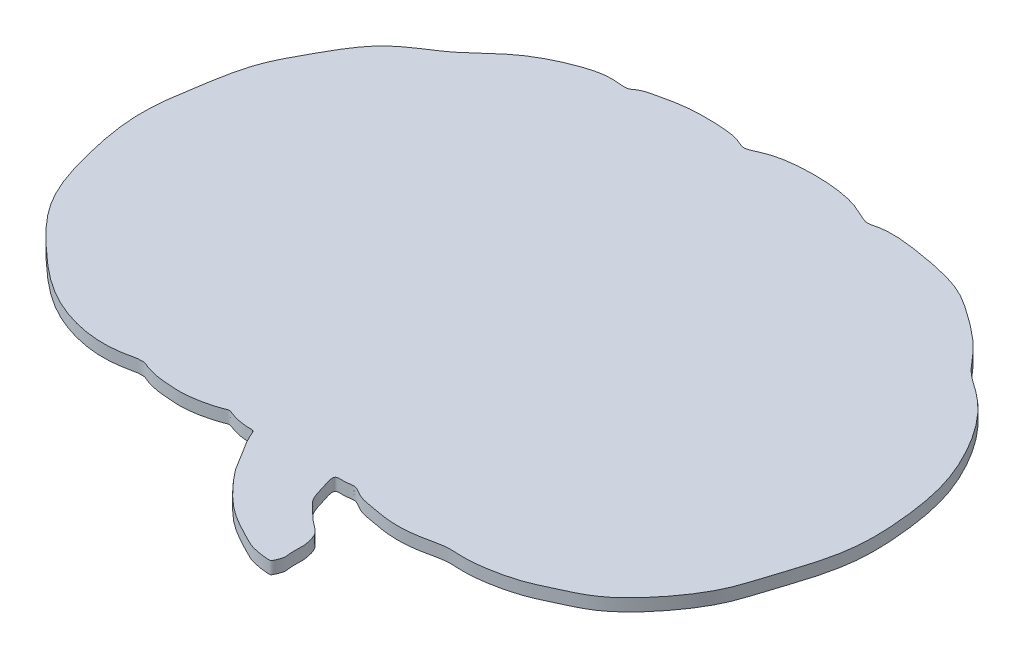
SolidWorks part; units mm, degrees
ref_plane "Front Plane" through (0, 0, 0) normal (0, 0, 1) x (1, 0, 0)
ref_plane "Top Plane" through (0, 0, 0) normal (0, 1, 0) x (1, 0, 0)
ref_plane "Right Plane" through (0, 0, 0) normal (1, 0, 0) x (0, 0, -1)
sketch "Sketch2" plane through (0, 0, 0) normal (0, 1, 0) x (1, 0, 0)
  line L1 (49.7423, 68.9433) -> (-50.2577, 68.9433)
  line L2 (49.7423, 68.9433) -> (49.7423, -31.0567)
  line L3 (49.7423, -31.0567) -> (-50.2577, -31.0567)
  line L4 (-50.2577, 68.9433) -> (-50.2577, -31.0567)
  dimension "D1" = 100
  dimension "D2" = 100
extrude "Boss-Extrude1" add sketch "Sketch2" against normal blind 1.6 contours L3 L4 L1 L2
sketch "Sketch3" plane through (0, 0, 0) normal (0, 1, 0) x (1, 0, 0)
  spline S0 degree 3 poles (39.5721, 42.257) (34.9334, 44.9388) (33.0549, 47.9676) (27.1539, 52.4068) (23.6183, 54.2453) (12.8535, 56.05) (12.2469, 54.3648) (8.8632, 56.5579) (3.2322, 57.229) (-2.1573, 56.7337) (-4.7434, 55.0346) (-5.8125, 56.3212) (-12.5293, 56.5654) (-14.9011, 55.9709) (-18.098, 55.3025) (-18.6107, 54.2404) (-21.5739, 55.1466) (-27.3012, 52.9405) (-30.5304, 50.8329) (-33.8528, 47.5719) (-36.4993, 45.839) (-40.2878, 43.3669) (-42.9009, 38.6086) (-45.9373, 33.1488) (-46.8674, 27.2209) (-48.0462, 20.1224) (-46.6576, 12.4714) (-44.1564, 4.4297) (-38.4634, -1.2895) (-31.8921, -6.8954) (-24.7194, -8.6108) (-20.5447, -7.4905) (-19.2274, -7.4461) (-19.2703, -7.6158) (-17.1574, -8.2499) (-14.5158, -8.441) (-13.8146, -8.4993) (-11.8488, -8.3271) (-8.8637, -7.5831) (-8.632, -7.213) (-7.945, -7.5529) (-7.2276, -7.7523) (-6.7896, -7.8809) (-5.268, -8.1402) (-4.6096, -7.8889) (-4.2905, -9.0327) (-3.3768, -10.5441) (-2.6602, -11.5774) (-1.8993, -13.2083) (0.6391, -16.2217) (3.4433, -18.7666) (7.1469, -20.6202) (8.3309, -21.3306) (11.0122, -21.6261) (11.1292, -21.4579) (11.6582, -20.2782) (11.4372, -19.5518) (11.5135, -17.9068) (11.4781, -17.5087) (11.0961, -15.4815) (9.4873, -14.592) (8.2524, -13.2573) (6.8833, -12.1596) (6.3727, -10.4919) (5.9746, -9.3639) (5.5963, -7.8509) (6.6295, -7.8907) (7.2936, -7.8781) (8.4116, -7.6139) (9.5894, -8.6536) (11.5588, -8.9155) (13.7903, -9.4088) (16.2935, -9.466) (18.7269, -9.0825) (20.9177, -8.5115) (23.4709, -8.7786) (26.541, -8.3946) (29.8278, -7.6048) (32.8512, -6.1187) (36.0861, -4.7021) (38.9007, -2.1734) (41.6136, 1.1521) (43.8391, 4.7237) (44.9954, 8.7847) (46.4496, 12.9853) (47.7007, 18.1611) (47.3842, 24.4441) (46.3581, 30.67) (43.4283, 37.129) (39.5721, 42.257) (34.9334, 44.9388) (33.0549, 47.9676) knots -0.070268 -0.048016 -0.015132 0 0.012581 0.021851 0.030192 0.037455 0.048804 0.056374 0.064159 0.072451 0.078983 0.085348 0.092328 0.100034 0.101849 0.110479 0.12368 0.143069 0.164046 0.177916 0.185937 0.201349 0.227825 0.246134 0.271974 0.295026 0.327362 0.359185 0.388614 0.416913 0.457725 0.463498 0.465473 0.471846 0.477112 0.480366 0.488425 0.493818 0.498708 0.507263 0.51094 0.513494 0.515546 0.518534 0.52291 0.528108 0.532184 0.537728 0.543639 0.560427 0.576701 0.589341 0.602104 0.605118 0.607695 0.610197 0.613016 0.616873 0.621646 0.628107 0.635129 0.64204 0.648736 0.654609 0.660605 0.664714 0.666968 0.670251 0.672851 0.679499 0.686579 0.695055 0.705493 0.71468 0.723007 0.730908 0.743483 0.757963 0.768985 0.781636 0.797819 0.811195 0.830417 0.844929 0.858875 0.880944 0.904719 0.929732 0.951984 0.984868 1 1.012581 1.021851 1.030192 only from (34.951, 45.3627) to (34.951, 45.3627)
  point P2 (10.8622, -16.5136)
  point P4 (11.4988, -19.5571)
  point P40 (11.4918, -18.2407)
  point P42 (0, 0)
  point P44 (8.038, -7.7612)
extrude "Cut-Extrude1" cut sketch "Sketch3" against normal blind 1.6 flip side to cut
